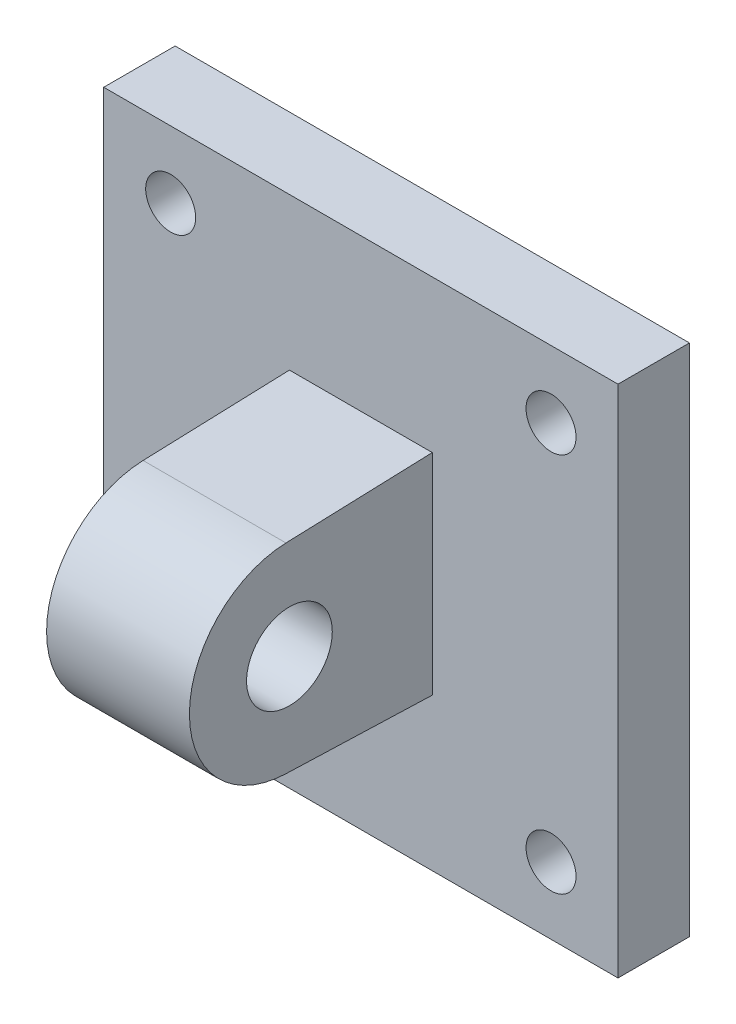
SolidWorks part; units mm, degrees
ref_plane "Front Plane" through (0, 0, 0) normal (0, 0, 1) x (1, 0, 0)
ref_plane "Top Plane" through (0, 0, 0) normal (0, 1, 0) x (1, 0, 0)
ref_plane "Right Plane" through (0, 0, 0) normal (1, 0, 0) x (0, 0, -1)
sketch "Sketch1" plane through (0, 0, 0) normal (0, 0, 1) x (1, 0, 0)
  line L0 (-57.15, -57.15) -> (57.15, 57.15) construction
  line L1 (-57.15, 57.15) -> (57.15, 57.15)
  line L2 (-57.15, 57.15) -> (-57.15, -57.15)
  line L3 (-57.15, -57.15) -> (57.15, -57.15)
  line L4 (57.15, 57.15) -> (57.15, -57.15)
  line L5 (-42.2672, 42.2672) -> (42.2672, -42.2672) construction
  line L6 (-42.2672, 42.2672) -> (42.2672, 42.2672) construction
  line L7 (-42.2672, 42.2672) -> (-42.2672, -42.2672) construction
  line L8 (-42.2672, -42.2672) -> (42.2672, -42.2672) construction
  line L9 (42.2672, 42.2672) -> (42.2672, -42.2672) construction
  line L10 (-15.875, 0) -> (15.875, 0) construction
  line L11 (15.875, 0) -> (31.75, 0) construction
  line L12 (-15.875, 0) -> (-31.75, 0) construction
  circle A0 centre (-42.2672, 42.2672) radius 5.5562
  circle A1 centre (42.2672, 42.2672) radius 5.5562
  circle A2 centre (42.2672, -42.2672) radius 5.5562
  circle A3 centre (-42.2672, -42.2672) radius 5.5562
  dimension "DD" = 11.1125
  dimension "E" = 114.3
  dimension "R" = 84.5344
  dimension "CW" = 15.875
  dimension "CB" = 31.75
sketch "Sketch2" plane through (0, 0, 0) normal (1, 0, 0) x (0, 0, -1)
  line L0 (0, 0) -> (-15.875, 0) construction
  line L1 (-15.875, 0) -> (-47.625, 0) construction
  line L2 (-47.625, 0) -> (-69.85, 0) construction
  circle A0 centre (-47.625, 0) radius 9.525
  dimension "CD" = 19.05
  dimension "F" = 15.875
  dimension "FL" = 47.625
  dimension "M" = 22.225
sketch "Sketch3" plane through (0, 0, 0) normal (0, 0, 1) x (1, 0, 0)
  line L4 (57.15, 57.15) -> (-57.15, 57.15)
  line L5 (57.15, -57.15) -> (57.15, 57.15)
  line L6 (-57.15, -57.15) -> (57.15, -57.15)
  line L7 (-57.15, 57.15) -> (-57.15, -57.15)
  line L8 (57.15, 57.15) -> (-57.15, 57.15)
  line L9 (57.15, -57.15) -> (57.15, 57.15)
  line L10 (-57.15, -57.15) -> (57.15, -57.15)
  line L11 (-57.15, 57.15) -> (-57.15, -57.15)
  circle A1 centre (-42.2672, -42.2672) radius 5.5562
  circle A2 centre (-42.2672, -42.2672) radius 5.5562
  circle A3 centre (42.2672, -42.2672) radius 5.5562
  circle A4 centre (42.2672, -42.2672) radius 5.5562
  circle A5 centre (42.2672, 42.2672) radius 5.5562
  circle A6 centre (42.2672, 42.2672) radius 5.5562
  circle A7 centre (-42.2672, 42.2672) radius 5.5562
  circle A8 centre (-42.2672, 42.2672) radius 5.5562
  dimension "D1" = 0
  dimension "D2" = 0
  dimension "D3" = 0
  dimension "D4" = 0
  dimension "D5" = 0
extrude "Boss-Extrude1" add sketch "Sketch3" along normal up to vertex (15.875 mm away) up to point (0, 0, 15.875)
sketch "Sketch4" plane through (0, 0, 0) normal (1, 0, 0) x (0, 0, -1)
  line L0 (-48.4006, 22.2115) -> (-15.875, 23.3473)
  line L1 (-15.875, 23.3473) -> (-15.875, -23.3473)
  line L2 (-48.4006, -22.2115) -> (-15.875, -23.3473)
  line L3 (-15.875, 0) -> (-47.625, 0) construction
  circle A0 centre (-47.625, 0) radius 9.525 construction
  circle A1 centre (-47.625, 0) radius 9.525
  arc A2 (-48.4006, 22.2115) -> (-48.4006, -22.2115) centre (-47.625, 0) ccw
  dimension "D1" = 2
extrude "Boss-Extrude2" add sketch "Sketch4" against normal up to vertex (15.875 mm away) and the other way up to vertex (15.875 mm away) up to point (-15.875, 0, 0) other way up to point (15.875, 0, 0)
